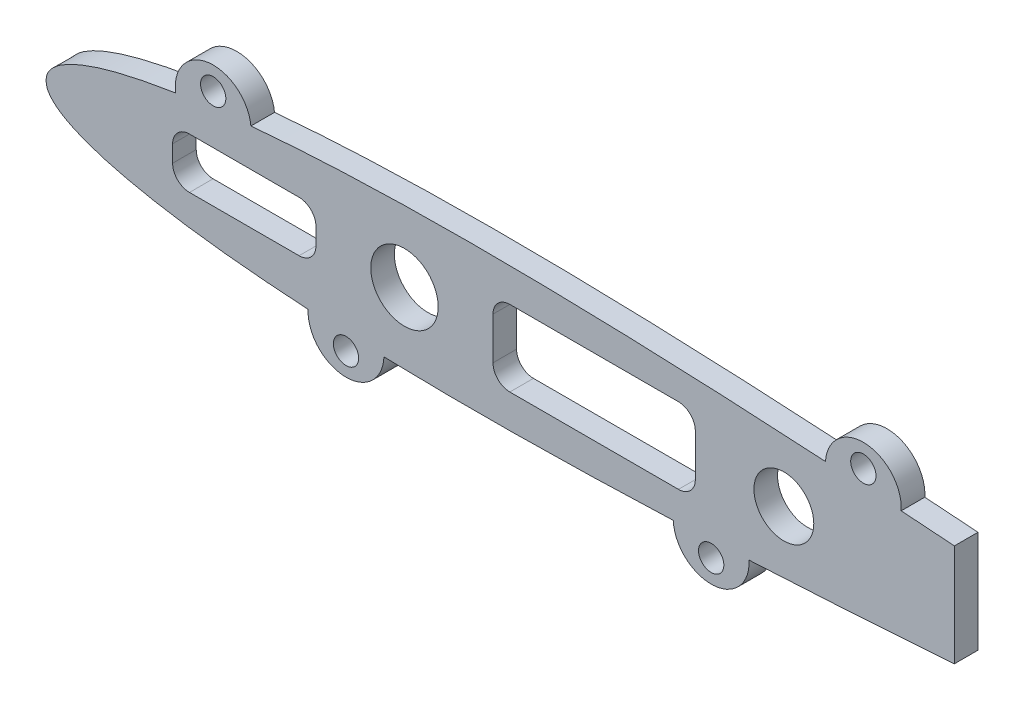
SolidWorks part; units mm, degrees
material "Фанера"
ref_plane "Front Plane" through (0, 0, 0) normal (0, 0, 1) x (1, 0, 0)
ref_plane "Top Plane" through (0, 0, 0) normal (0, 1, 0) x (1, 0, 0)
ref_plane "Right Plane" through (0, 0, 0) normal (1, 0, 0) x (0, 0, -1)
curve "Кривая1"
  spline degree 3 poles (110, 0, 0) (110.0276, -0.2367, 0) (110.0855, -0.7342, 0) (110.5302, -1.4271, 0) (111.1963, -2.0786, 0) (112.1098, -2.7013, 0) (113.2568, -3.2993, 0) (114.6379, -3.8731, 0) (116.2477, -4.4214, 0) (118.0813, -4.9426, 0) (120.1331, -5.4348, 0) (122.3972, -5.8961, 0) (124.8672, -6.3247, 0) (127.537, -6.7187, 0) (130.3997, -7.0764, 0) (133.4488, -7.3965, 0) (136.6771, -7.6776, 0) (140.0777, -7.9187, 0) (143.6433, -8.119, 0) (147.3662, -8.278, 0) (151.2389, -8.3955, 0) (155.2534, -8.4715, 0) (159.4016, -8.5065, 0) (163.6751, -8.501, 0) (168.0653, -8.456, 0) (172.5632, -8.3725, 0) (177.1595, -8.252, 0) (181.8446, -8.096, 0) (186.6087, -7.9062, 0) (191.4413, -7.6846, 0) (196.3316, -7.4331, 0) (201.2684, -7.1538, 0) (206.2396, -6.8489, 0) (211.233, -6.5205, 0) (216.2352, -6.1709, 0) (221.2323, -5.8022, 0) (226.2093, -5.417, 0) (231.1504, -5.0174, 0) (236.0382, -4.6058, 0) (240.8542, -4.1849, 0) (245.5777, -3.7574, 0) (250.1862, -3.3262, 0) (254.6542, -2.8948, 0) (258.9526, -2.4672, 0) (263.0477, -2.0479, 0) (266.899, -1.6426, 0) (270.4558, -1.2586, 0) (273.6512, -0.9053, 0) (276.3854, -0.5964, 0) (278.4526, -0.359, 0) (279.592, -0.2261, 0) (280, -0.1785, 0) knots 0 0 0 0 0.004099 0.008615 0.013935 0.020278 0.027753 0.03641 0.046266 0.05732 0.069559 0.082963 0.097507 0.113164 0.129903 0.14769 0.166492 0.186272 0.206992 0.228612 0.251092 0.274389 0.298458 0.323254 0.348728 0.37483 0.401509 0.42871 0.456376 0.484448 0.512864 0.541558 0.570462 0.599504 0.628607 0.65769 0.686667 0.715445 0.743924 0.771995 0.79954 0.826428 0.852512 0.877624 0.901571 0.924121 0.944989 0.963804 0.980044 0.992855 1 1 1 1
curve "Кривая2"
  spline degree 3 poles (280, 0.1785, 0) (279.592, 0.2261, 0) (278.4526, 0.359, 0) (276.3854, 0.5964, 0) (273.6512, 0.9053, 0) (270.4558, 1.2586, 0) (266.899, 1.6426, 0) (263.0477, 2.0479, 0) (258.9526, 2.4672, 0) (254.6542, 2.8948, 0) (250.1862, 3.3262, 0) (245.5777, 3.7574, 0) (240.8542, 4.1849, 0) (236.0382, 4.6058, 0) (231.1504, 5.0174, 0) (226.2093, 5.417, 0) (221.2323, 5.8022, 0) (216.2352, 6.1709, 0) (211.233, 6.5205, 0) (206.2396, 6.8489, 0) (201.2684, 7.1538, 0) (196.3316, 7.4331, 0) (191.4413, 7.6846, 0) (186.6087, 7.9062, 0) (181.8446, 8.096, 0) (177.1595, 8.252, 0) (172.5632, 8.3725, 0) (168.0653, 8.456, 0) (163.6751, 8.501, 0) (159.4016, 8.5065, 0) (155.2534, 8.4715, 0) (151.2389, 8.3955, 0) (147.3662, 8.278, 0) (143.6433, 8.119, 0) (140.0777, 7.9187, 0) (136.6771, 7.6776, 0) (133.4488, 7.3965, 0) (130.3997, 7.0764, 0) (127.537, 6.7187, 0) (124.8672, 6.3247, 0) (122.3972, 5.8961, 0) (120.1331, 5.4348, 0) (118.0813, 4.9426, 0) (116.2477, 4.4214, 0) (114.6379, 3.8731, 0) (113.2568, 3.2993, 0) (112.1098, 2.7013, 0) (111.1963, 2.0786, 0) (110.5302, 1.4271, 0) (110.0855, 0.7342, 0) (110.0276, 0.2367, 0) (110, 0, 0) knots 0 0 0 0 0.007145 0.019956 0.036196 0.055011 0.075879 0.098429 0.122376 0.147488 0.173572 0.20046 0.228005 0.256076 0.284555 0.313333 0.34231 0.371393 0.400496 0.429538 0.458442 0.487136 0.515552 0.543624 0.57129 0.598491 0.62517 0.651272 0.676746 0.701542 0.725611 0.748908 0.771388 0.793008 0.813728 0.833508 0.85231 0.870097 0.886836 0.902493 0.917037 0.930441 0.94268 0.953734 0.96359 0.972247 0.979722 0.986065 0.991385 0.995901 1 1 1 1
sketch "Эскиз1" plane through (0, 0, 0) normal (0, 0, 1) x (1, 0, 0)
  line L0 (105.1708, 0) -> (280.7263, 0) construction
  line L1 (280.0739, 0) -> (280.0739, 24.3846) construction
  line L2 (110, -5.3315) -> (110, 17.5304) construction
  line L3 (152.5185, 18.8331) -> (152.5185, -21.3473) construction
  line L4 (223.3826, 13.2402) -> (223.3826, -18.4275) construction
  line L5 (217.7476, 6.0581) -> (217.7476, -6.0581)
  line L6 (127.0185, -3) -> (140.0185, -3)
  line L7 (125.0185, -1) -> (125.0185, 1)
  line L8 (127.0185, 3) -> (140.0185, 3)
  line L9 (142.0185, -1) -> (142.0185, 1)
  line L10 (125.0185, -3) -> (142.0185, 3) construction
  line L11 (125.0185, 3) -> (142.0185, -3) construction
  line L12 (165.0185, -4.5) -> (185.0185, -4.5)
  line L13 (163.0185, -2.5) -> (163.0185, 2.5)
  line L14 (165.0185, 4.5) -> (185.0185, 4.5)
  line L15 (187.0185, -2.5) -> (187.0185, 2.5)
  line L16 (163.0185, -4.5) -> (187.0185, 4.5) construction
  line L17 (163.0185, 4.5) -> (187.0185, -4.5) construction
  arc A0 (280, 0.1785) -> (280, -0.1785) centre (279.8215, 0) cw
  circle A1 centre (152.5185, 0) radius 4
  circle A2 centre (197.5185, 0) radius 3.55
  arc A3 (185.0185, 4.5) -> (187.0185, 2.5) centre (185.0185, 2.5) cw
  arc A4 (185.0185, -4.5) -> (187.0185, -2.5) centre (185.0185, -2.5) ccw
  arc A5 (165.0185, -4.5) -> (163.0185, -2.5) centre (165.0185, -2.5) cw
  arc A6 (163.0185, 2.5) -> (165.0185, 4.5) centre (165.0185, 2.5) cw
  arc A7 (125.0185, 1) -> (127.0185, 3) centre (127.0185, 1) cw
  arc A8 (127.0185, -3) -> (125.0185, -1) centre (127.0185, -1) cw
  arc A9 (140.0185, -3) -> (142.0185, -1) centre (140.0185, -1) ccw
  arc A10 (140.0185, 3) -> (142.0185, 1) centre (140.0185, 1) cw
  arc A11 (223.3826, 5.635) -> (223.3826, -5.635) centre (223.3826, 0) ccw
  circle A12 centre (223.3826, 0) radius 1
  arc A13 (134.3056, 7.4673) -> (125.371, 6.3931) centre (129.8299, 7) ccw
  arc A14 (141.0932, -7.9724) -> (150.0847, -8.3577) centre (145.5874, -8.2) ccw
  arc A15 (211.4375, 6.5031) -> (202.4559, 7.0792) centre (206.9473, 6.8) ccw
  arc A16 (184.4033, -7.9928) -> (193.3939, -7.5829) centre (188.8991, -7.8) ccw
  circle A17 centre (129.8299, 8.8) radius 1.5
  circle A18 centre (145.5874, -10) radius 1.5
  circle A19 centre (188.8991, -9.6) radius 1.5
  circle A20 centre (206.9473, 8.6) radius 1.5
  spline S0 degree 3 poles (110, 0) (110.0276, -0.2367) (110.0855, -0.7342) (110.5302, -1.4271) (111.1963, -2.0786) (112.1098, -2.7013) (113.2568, -3.2993) (114.6379, -3.8731) (116.2477, -4.4214) (118.0813, -4.9426) (120.1331, -5.4348) (122.3972, -5.8961) (124.8672, -6.3247) (127.537, -6.7187) (130.3997, -7.0764) (133.4488, -7.3965) (136.6771, -7.6776) (140.0777, -7.9187) (143.6433, -8.119) (147.3662, -8.278) (151.2389, -8.3955) (155.2534, -8.4715) (159.4016, -8.5065) (163.6751, -8.501) (168.0653, -8.456) (172.5632, -8.3725) (177.1595, -8.252) (181.8446, -8.096) (186.6087, -7.9062) (191.4413, -7.6846) (196.3316, -7.4331) (201.2684, -7.1538) (206.2396, -6.8489) (211.233, -6.5205) (216.2352, -6.1709) (221.2323, -5.8022) (226.2093, -5.417) (231.1504, -5.0174) (236.0382, -4.6058) (240.8542, -4.1849) (247.0711, -3.6222) (253.1161, -3.0479) (258.9526, -2.4672) (263.0477, -2.0479) (266.899, -1.6426) (270.4558, -1.2586) (273.6512, -0.9053) (276.3854, -0.5964) (278.4526, -0.359) (279.592, -0.2261) (280, -0.1785) knots 0 0 0 0 0.004099 0.008615 0.013935 0.020278 0.027753 0.03641 0.046266 0.05732 0.069559 0.082963 0.097507 0.113164 0.129903 0.14769 0.166492 0.186272 0.206992 0.228612 0.251092 0.274389 0.298458 0.323254 0.348728 0.37483 0.401509 0.42871 0.456376 0.484448 0.512864 0.541558 0.570462 0.599504 0.628607 0.65769 0.686667 0.715445 0.743924 0.771995 0.79954 0.852512 0.877624 0.901571 0.924121 0.944989 0.963804 0.980044 0.992855 1 1 1 1 construction
  spline S1 degree 3 poles (280, 0.1785) (279.592, 0.2261) (278.4526, 0.359) (276.3854, 0.5964) (273.6512, 0.9053) (270.4558, 1.2586) (266.899, 1.6426) (263.0477, 2.0479) (258.9526, 2.4672) (253.1161, 3.0479) (247.0711, 3.6222) (240.8542, 4.1849) (236.0382, 4.6058) (231.1504, 5.0174) (226.2093, 5.417) (221.2323, 5.8022) (216.2352, 6.1709) (211.233, 6.5205) (206.2396, 6.8489) (201.2684, 7.1538) (196.3316, 7.4331) (191.4413, 7.6846) (186.6087, 7.9062) (181.8446, 8.096) (177.1595, 8.252) (172.5632, 8.3725) (168.0653, 8.456) (163.6751, 8.501) (159.4016, 8.5065) (155.2534, 8.4715) (151.2389, 8.3955) (147.3662, 8.278) (143.6433, 8.119) (140.0777, 7.9187) (136.6771, 7.6776) (133.4488, 7.3965) (130.3997, 7.0764) (127.537, 6.7187) (124.8672, 6.3247) (122.3972, 5.8961) (120.1331, 5.4348) (118.0813, 4.9426) (116.2477, 4.4214) (114.6379, 3.8731) (113.2568, 3.2993) (112.1098, 2.7013) (111.1963, 2.0786) (110.5302, 1.4271) (110.0855, 0.7342) (110.0276, 0.2367) (110, 0) knots 0 0 0 0 0.007145 0.019956 0.036196 0.055011 0.075879 0.098429 0.122376 0.147488 0.20046 0.228005 0.256076 0.284555 0.313333 0.34231 0.371393 0.400496 0.429538 0.458442 0.487136 0.515552 0.543624 0.57129 0.598491 0.62517 0.651272 0.676746 0.701542 0.725611 0.748908 0.771388 0.793008 0.813728 0.833508 0.85231 0.870097 0.886836 0.902493 0.917037 0.930441 0.94268 0.953734 0.96359 0.972247 0.979722 0.986065 0.991385 0.995901 1 1 1 1 construction
  spline S2 degree 3 poles (110, 0) (110.0276, -0.2367) (110.0855, -0.7342) (110.5302, -1.4271) (111.1963, -2.0786) (112.1098, -2.7013) (113.2568, -3.2993) (114.6379, -3.8731) (116.2477, -4.4214) (118.0813, -4.9426) (120.1331, -5.4348) (122.3972, -5.8961) (124.8672, -6.3247) (127.537, -6.7187) (130.3997, -7.0764) (133.4488, -7.3965) (136.6771, -7.6776) (139.2456, -7.8597) (140.7369, -7.9513) (141.0932, -7.9724) knots 0 0 0 0 0.004099 0.008615 0.013935 0.020278 0.027753 0.03641 0.046266 0.05732 0.069559 0.082963 0.097507 0.113164 0.129903 0.14769 0.166492 0.186272 0.192481 0.192481 0.192481 0.192481
  spline S3 degree 3 poles (280, 0.1785) (279.592, 0.2261) (278.4526, 0.359) (276.3854, 0.5964) (273.6512, 0.9053) (270.4558, 1.2586) (266.899, 1.6426) (263.0477, 2.0479) (258.9526, 2.4672) (253.1161, 3.0479) (247.0711, 3.6222) (240.8542, 4.1849) (236.0382, 4.6058) (231.1504, 5.0174) (226.2093, 5.417) (221.2323, 5.8022) (216.3046, 6.1657) (213.0372, 6.3944) (211.4375, 6.5031) knots 0 0 0 0 0.007145 0.019956 0.036196 0.055011 0.075879 0.098429 0.122376 0.147488 0.20046 0.228005 0.256076 0.284555 0.313333 0.34231 0.371393 0.399286 0.399286 0.399286 0.399286
  spline S4 degree 3 poles (150.0847, -8.3577) (150.4538, -8.368) (152.1618, -8.413) (155.2534, -8.4715) (159.4016, -8.5065) (163.6751, -8.501) (168.0653, -8.456) (172.5632, -8.3725) (177.1595, -8.252) (181.1171, -8.1202) (183.5415, -8.0273) (184.4033, -7.9928) knots 0.244668 0.244668 0.244668 0.244668 0.251092 0.274389 0.298458 0.323254 0.348728 0.37483 0.401509 0.42871 0.443713 0.443713 0.443713 0.443713
  spline S5 degree 3 poles (125.371, 6.3931) (125.1826, 6.3638) (124.1683, 6.2034) (122.3972, 5.8961) (120.1331, 5.4348) (118.0813, 4.9426) (116.2477, 4.4214) (114.6379, 3.8731) (113.2568, 3.2993) (112.1098, 2.7013) (111.1963, 2.0786) (110.5302, 1.4271) (110.0855, 0.7342) (110.0276, 0.2367) (110, 0) knots 0.899175 0.899175 0.899175 0.899175 0.902493 0.917037 0.930441 0.94268 0.953734 0.96359 0.972247 0.979722 0.986065 0.991385 0.995901 1 1 1 1
  spline S6 degree 3 poles (202.4559, 7.0792) (202.056, 7.1032) (200.0095, 7.225) (196.3316, 7.4331) (191.4413, 7.6846) (186.6087, 7.9062) (181.8446, 8.096) (177.1595, 8.252) (172.5632, 8.3725) (168.0653, 8.456) (163.6751, 8.501) (159.4016, 8.5065) (155.2534, 8.4715) (151.2389, 8.3955) (147.3662, 8.278) (143.6433, 8.119) (140.0777, 7.9187) (136.9824, 7.6992) (135.0773, 7.5376) (134.3056, 7.4673) knots 0.451472 0.451472 0.451472 0.451472 0.458442 0.487136 0.515552 0.543624 0.57129 0.598491 0.62517 0.651272 0.676746 0.701542 0.725611 0.748908 0.771388 0.793008 0.813728 0.833508 0.846987 0.846987 0.846987 0.846987
  spline S7 degree 3 poles (193.3939, -7.5829) (194.3678, -7.5334) (196.9889, -7.3959) (201.2684, -7.1538) (206.2396, -6.8489) (211.233, -6.5205) (216.2352, -6.1709) (221.2323, -5.8022) (226.2093, -5.417) (231.1504, -5.0174) (236.0382, -4.6058) (240.8542, -4.1849) (247.0711, -3.6222) (253.1161, -3.0479) (258.9526, -2.4672) (263.0477, -2.0479) (266.899, -1.6426) (270.4558, -1.2586) (273.6512, -0.9053) (276.3854, -0.5964) (278.4526, -0.359) (279.592, -0.2261) (280, -0.1785) knots 0.4959 0.4959 0.4959 0.4959 0.512864 0.541558 0.570462 0.599504 0.628607 0.65769 0.686667 0.715445 0.743924 0.771995 0.79954 0.852512 0.877624 0.901571 0.924121 0.944989 0.963804 0.980044 0.992855 1 1 1 1
  point P19 (175.0185, 0)
  point P22 (133.5185, 0)
  point P31 (223.3826, -5.635)
  point P54 (223.3826, 5.635)
  point P55 (223.3826, -5.635)
  point P56 (223.3826, 5.635)
  dimension "D1" = 0.2524
  dimension "D3" = 8
  dimension "D13" = 2
  dimension "D14" = 5.635
  dimension "D15" = 2
  dimension "D16" = 9
  dimension "D21" = 3
  dimension "D26" = 7.1
  dimension "D2" = 170.0739
  dimension "D4" = 42.5185
  dimension "D5" = 56.6913
  dimension "D6" = 45
  dimension "D7" = 6
  dimension "D8" = 17
  dimension "D9" = 19
  dimension "D10" = 22.5
  dimension "D11" = 9
  dimension "D12" = 24
  dimension "D17" = 7
  dimension "D18" = 8.2
  dimension "D19" = 7.8
  dimension "D20" = 6.8
  dimension "D22" = 1.8
  dimension "D23" = 1.8
  dimension "D24" = 1.8
  dimension "D25" = 1.8
extrude "Бобышка-Вытянуть1" add sketch "Эскиз1" along normal mid plane 2.8 contours L5 S3 S2 L8 A10 L9 A9 L6 A8 L7 A7 L13 A6 L14 A3 L15 A4 L12 A5 A1 A2
equation "\"D4@Эскиз1\"=\"D2@Эскиз1\"/4"
equation "\"D5@Эскиз1\"=\"D2@Эскиз1\"/3"
equation "\"D10@Эскиз1\"=\"D6@Эскиз1\"/2"
